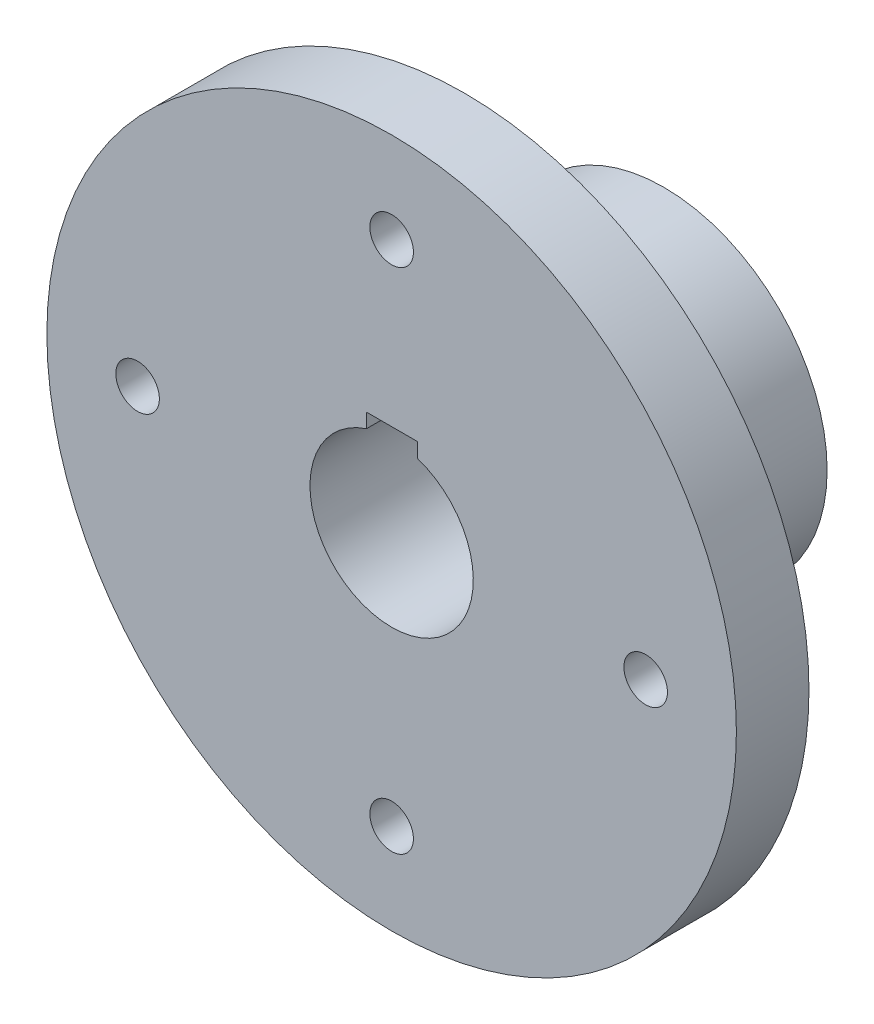
SolidWorks part; units mm, degrees
ref_plane "Front Plane" through (0, 0, 0) normal (0, 0, 1) x (1, 0, 0)
ref_plane "Top Plane" through (0, 0, 0) normal (0, 1, 0) x (1, 0, 0)
ref_plane "Right Plane" through (0, 0, 0) normal (1, 0, 0) x (0, 0, -1)
sketch "Sketch1" plane through (0, 0, 0) normal (0, 0, 1) x (1, 0, 0)
  line L0 (0, 118.5445) -> (0, -124.7617) construction
  line L1 (-124.6211, 0) -> (121.4834, 0) construction
  circle A1 centre (0, 0) radius 95
  dimension "D1" = 190
extrude "Boss-Extrude1" add sketch "Sketch1" along normal blind 20 contours A1
sketch "Sketch2" plane through (0, 0, 20) normal (0, 0, 1) x (1, 0, 0)
  line L0 (0, 101.9644) -> (0, -107.2004) construction
  line L1 (-115.1922, 0) -> (133.6561, 0) construction
  circle A0 centre (0, 70) radius 6
  circle A1 centre (70, 0) radius 6
  circle A2 centre (0, -70) radius 6
  circle A3 centre (-70, 0) radius 6
  dimension "D1" = 12
extrude "Cut-Extrude1" cut sketch "Sketch2" against normal blind 20
sketch "Sketch3" plane through (0, 0, 20) normal (0, 0, 1) x (1, 0, 0)
  line L0 (0, 88.4777) -> (0, -119.0336) construction
  line L1 (-109.6806, 0) -> (169.4814, 0) construction
  line L2 (-6.9403, 22.4741) -> (-6.9403, 21.4029)
  line L3 (7.0597, 22.4741) -> (7.0597, 21.3638)
  line L4 (-6.9403, 25.3741) -> (7.0597, 25.3741)
  line L5 (-6.9403, 25.3741) -> (-6.9403, 22.4741)
  line L7 (7.0597, 25.3741) -> (7.0597, 22.4741)
  line L8 (-6.9403, 25.3741) -> (7.0597, 22.4741) construction
  line L9 (-6.9403, 22.4741) -> (7.0597, 25.3741) construction
  arc A0 (-6.9403, 21.4029) -> (7.0597, 21.3638) centre (0, 0) ccw
  dimension "D1" = 45
sketch "Sketch4" plane through (0, 0, 20) normal (0, 0, 1) x (1, 0, 0)
sketch "Sketch5" plane through (0, 0, 0) normal (0, 0, -1) x (-1, 0, 0)
  circle A0 centre (0, 0) radius 45
extrude "Boss-Extrude3" add sketch "Sketch5" along normal blind 55
extrude "Cut-Extrude2" cut sketch "Sketch3" against normal blind 75
